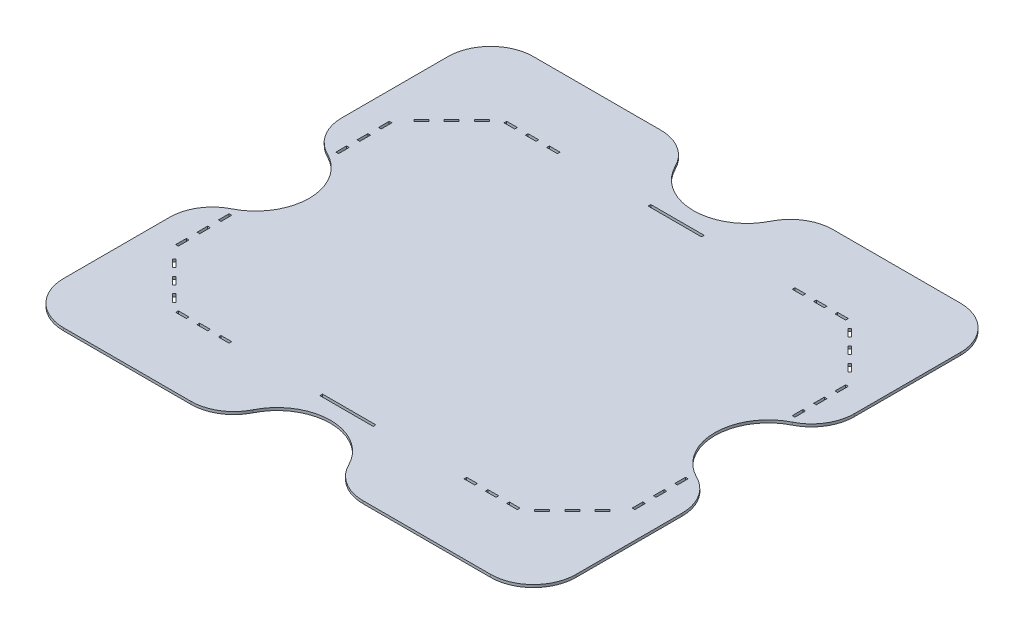
SolidWorks part; units mm, degrees
ref_plane "Front Plane" through (0, 0, 0) normal (0, 0, 1) x (1, 0, 0)
ref_plane "Top Plane" through (0, 0, 0) normal (0, 1, 0) x (1, 0, 0)
ref_plane "Right Plane" through (0, 0, 0) normal (1, 0, 0) x (0, 0, -1)
sketch "Sketch1" plane through (0, 0, 0) normal (0, 1, 0) x (1, 0, 0)
  line L1 (-254, -279.4) -> (254, -279.4)
  line L2 (-304.8, -228.6) -> (-304.8, 228.6)
  line L3 (-254, 279.4) -> (254, 279.4)
  line L4 (304.8, -228.6) -> (304.8, 228.6)
  line L5 (-304.8, -279.4) -> (304.8, 279.4) construction
  line L6 (-304.8, 279.4) -> (304.8, -279.4) construction
  arc A0 (63.5, 279.4) -> (-63.5, 279.4) centre (0, 279.4) cw
  arc A1 (304.8, 63.5) -> (304.8, -63.5) centre (304.8, 0) ccw
  arc A2 (-63.5, -279.4) -> (63.5, -279.4) centre (0, -279.4) cw
  arc A3 (-304.8, 63.5) -> (-304.8, -63.5) centre (-304.8, 0) cw
  arc A4 (254, 279.4) -> (304.8, 228.6) centre (254, 228.6) cw
  arc A5 (254, -279.4) -> (304.8, -228.6) centre (254, -228.6) ccw
  arc A6 (-254, -279.4) -> (-304.8, -228.6) centre (-254, -228.6) cw
  arc A7 (-304.8, 228.6) -> (-254, 279.4) centre (-254, 228.6) cw
  point P0 (0, 0)
  dimension "D3" = 63.5
  dimension "D4" = 50.8
  dimension "D1" = 609.6
  dimension "D2" = 558.8
extrude "Boss-Extrude1" add sketch "Sketch1" along normal blind 3.175 contours A7 L2 A3 A6 L1 A2 A5 L4 A1 A4 L3 A0
fillet "Fillet1" radius 50.8 8 edges at (63.5, 1.5875, 279.4) (-63.5, 1.5875, 279.4) (-304.8, 1.5875, 63.5) (-304.8, 1.5875, -63.5) (-63.5, 1.5875, -279.4) (63.5, 1.5875, -279.4) (304.8, 1.5875, -63.5) (304.8, 1.5875, 63.5)
sketch "Sketch2" plane through (0, 3.175, 0) normal (0, 1, 0) x (1, 0, 0)
  line L0 (-177.8, 196.85) -> (-177.8, 193.675)
  line L5 (-203.2, 196.85) -> (-190.5, 196.85)
  line L6 (-203.2, 196.85) -> (-203.2, 193.675)
  line L7 (-203.2, 193.675) -> (-190.5, 193.675)
  line L8 (-190.5, 196.85) -> (-190.5, 193.675)
  line L9 (-203.2, 196.85) -> (-190.5, 193.675) construction
  line L10 (-203.2, 193.675) -> (-190.5, 196.85) construction
  line L11 (-177.8, 196.85) -> (-165.1, 196.85)
  line L12 (-165.1, 196.85) -> (-165.1, 193.675)
  line L13 (-177.8, 193.675) -> (-165.1, 193.675)
  line L14 (-152.4, 196.85) -> (-152.4, 193.675)
  line L15 (-152.4, 196.85) -> (-139.7, 196.85)
  line L16 (-139.7, 196.85) -> (-139.7, 193.675)
  line L17 (-152.4, 193.675) -> (-139.7, 193.675)
  point P0 (-196.85, 195.2625)
  dimension "D1" = 12.7
  dimension "D2" = 3.175
  dimension "D3" = 193.675
  dimension "D4" = 203.2
  dimension "D6" = 12.7
  dimension "D5" = 3
extrude "Cut-Extrude1" cut sketch "Sketch2" against normal blind 3.175
mirror "Mirror1" about plane through (0, 0, 0) normal (0, 0, 1) of "Cut-Extrude1"
mirror "Mirror2" about plane through (0, 0, 0) normal (1, 0, 0) of "Cut-Extrude1", "Mirror1"
sketch "Sketch3" plane through (0, 3.175, 0) normal (0, 1, 0) x (1, 0, 0)
  line L0 (-251.3697, 152.653) -> (-260.35, 143.6728)
  line L1 (-260.35, 143.6728) -> (-258.1049, 141.4277)
  line L2 (-258.1049, 141.4277) -> (-249.1247, 150.408)
  line L3 (-249.1247, 150.408) -> (-251.3697, 152.653)
  line L4 (-304.8, 96.9777) -> (-122.3777, 279.4) construction
  line L7 (-233.4092, 170.6135) -> (-242.3895, 161.6333)
  line L8 (-242.3895, 161.6333) -> (-240.1444, 159.3882)
  line L9 (-240.1444, 159.3882) -> (-231.1642, 168.3685)
  line L10 (-231.1642, 168.3685) -> (-233.4092, 170.6135)
  line L11 (-213.2037, 186.329) -> (-222.1839, 177.3487)
  line L12 (-222.1839, 177.3487) -> (-224.429, 179.5938)
  line L13 (-224.429, 179.5938) -> (-215.4487, 188.574)
  line L14 (-215.4487, 188.574) -> (-213.2037, 186.329)
  line L15 (-289.921, 264.521) -> (-213.5888, 188.1888) construction
  line L16 (-254, 279.4) -> (-102.3907, 279.4) construction
  line L17 (-304.8, 102.3907) -> (-304.8, 228.6) construction
  arc A1 (-254, 279.4) -> (-304.8, 228.6) centre (-254, 228.6) ccw construction
  point P10 (-250.2472, 151.5305)
  point P15 (-232.2867, 169.491)
  point P20 (-214.3262, 187.4515)
  point P24 (-289.921, 264.521)
  point P25 (-254, 200.5023)
  point P29 (-203.2, 279.4)
  point P30 (0, 0)
  dimension "D1" = 12.7
  dimension "D2" = 3.175
  dimension "D3" = 12.7
  dimension "D4" = 12.7
  dimension "D5" = 45
  dimension "D6" = 107.95
  dimension "D7" = 44.45
extrude "Cut-Extrude2" cut sketch "Sketch3" against normal blind 3.175
sketch "Sketch4" plane through (0, 3.175, 0) normal (0, 1, 0) x (1, 0, 0)
  line L0 (-139.7, 193.675) -> (-139.7, 196.85) construction
  line L1 (-31.75, 193.675) -> (31.75, 193.675)
  line L2 (-31.75, 193.675) -> (-31.75, 196.85)
  line L3 (-31.75, 196.85) -> (31.75, 196.85)
  line L4 (31.75, 193.675) -> (31.75, 196.85)
  line L5 (-31.75, 193.675) -> (31.75, 196.85) construction
  line L6 (-31.75, 196.85) -> (31.75, 193.675) construction
  line L8 (-55, 0) -> (55, 0) construction
  line L9 (-31.75, -196.85) -> (31.75, -196.85)
  line L10 (31.75, -193.675) -> (31.75, -196.85)
  line L11 (-31.75, -193.675) -> (31.75, -193.675)
  line L12 (-31.75, -193.675) -> (-31.75, -196.85)
  point P0 (0, 195.2625)
  point P9 (-139.7, 195.2625)
  dimension "D1" = 63.5
  dimension "D2" = 3.175
extrude "Cut-Extrude3" cut sketch "Sketch4" against normal blind 3.175
mirror "Mirror4" about plane through (0, 0, 0) normal (0, 0, 1) of "Cut-Extrude2"
mirror "Mirror5" about plane through (0, 0, 0) normal (1, 0, 0) of "Cut-Extrude3", "Mirror4"
sketch "Sketch5" plane through (0, 3.175, 0) normal (0, 1, 0) x (1, 0, 0)
  line L1 (-273.05, -88.9) -> (-269.875, -88.9)
  line L2 (-273.05, -88.9) -> (-273.05, -101.6)
  line L3 (-273.05, -101.6) -> (-269.875, -101.6)
  line L4 (-269.875, -88.9) -> (-269.875, -101.6)
  line L12 (-273.05, -63.5) -> (-273.05, -76.2)
  line L13 (-273.05, -63.5) -> (-269.875, -63.5)
  line L14 (-269.875, -63.5) -> (-269.875, -76.2)
  line L15 (-273.05, -76.2) -> (-269.875, -76.2)
  line L17 (-273.05, -114.3) -> (-269.875, -114.3)
  line L18 (-273.05, -114.3) -> (-273.05, -127)
  line L19 (-273.05, -127) -> (-269.875, -127)
  line L20 (-269.875, -114.3) -> (-269.875, -127)
  point P13 (-271.4625, -101.6)
  dimension "D1" = 12.7
  dimension "D2" = 3.175
  dimension "D3" = 101.6
  dimension "D5" = 12.7
  dimension "D6" = 269.875
  dimension "D7" = 3.175
  dimension "D8" = 12.7
  dimension "D9" = 12.7
  dimension "D4" = 2
extrude "Cut-Extrude4" cut sketch "Sketch5" against normal blind 3.175
mirror "Mirror6" about plane through (0, 0, 0) normal (1, 0, 0) of "Cut-Extrude4"
mirror "Mirror7" about plane through (0, 0, 0) normal (0, 0, 1) of "Cut-Extrude4", "Mirror6"
